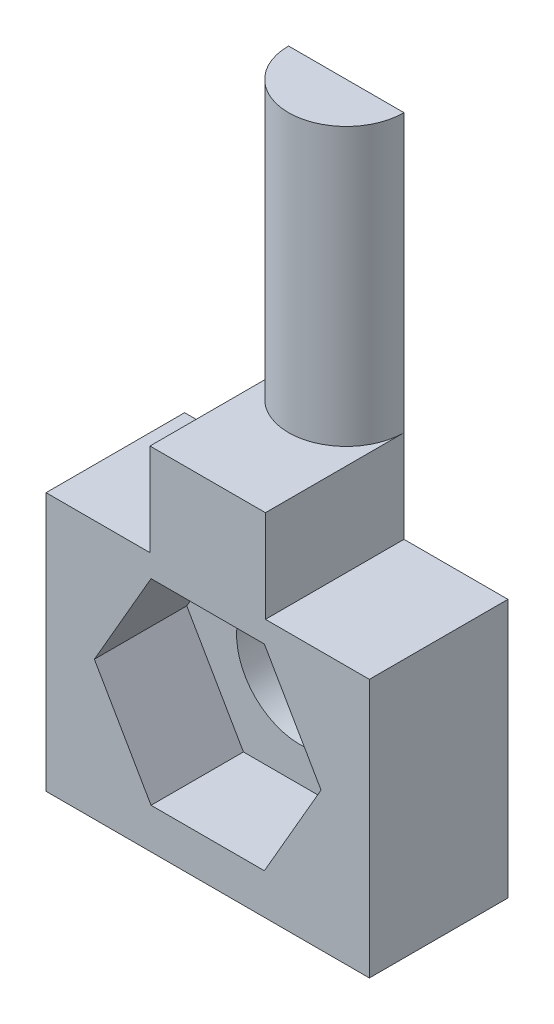
SolidWorks part; units mm, degrees
ref_plane "Alzado" through (0, 0, 0) normal (0, 0, 1) x (1, 0, 0)
ref_plane "Planta" through (0, 0, 0) normal (0, 1, 0) x (1, 0, 0)
ref_plane "Vista lateral" through (0, 0, 0) normal (1, 0, 0) x (0, 0, -1)
sketch "Croquis1" plane through (0, 0, 0) normal (0, 0, 1) x (1, 0, 0)
  line L0 (-9.5, 11.2) -> (-14, 11.2)
  line L1 (0, 0) -> (-14, 0)
  line L2 (0, 0) -> (0, 11.2)
  line L3 (0, 11.2) -> (-4.5, 11.2)
  line L4 (-14, 0) -> (-14, 11.2)
  line L6 (-9.5, 11.2) -> (-9.5, 15.2)
  line L7 (-9.5, 15.2) -> (-4.5, 15.2)
  line L8 (-4.5, 11.2) -> (-4.5, 15.2)
  circle A0 centre (-7, 6) radius 2.75
  dimension "D3" = 5.5
  dimension "D1" = 14
  dimension "D2" = 11.2
  dimension "D4" = 5
  dimension "D5" = 4
  dimension "D6" = 5.2
extrude "Saliente-Extruir1" add sketch "Croquis1" along normal blind 6
sketch "Croquis2" plane through (0, 15.2, 0) normal (0, 1, 0) x (1, 0, 0)
  line L0 (-4.5, 0) -> (-9.5, 0) construction
  line L1 (-9.5, 0) -> (-4.5, 0)
  arc A0 (-9.5, 0) -> (-4.5, 0) centre (-7, 0) ccw
extrude "Saliente-Extruir2" add sketch "Croquis2" along normal blind 12
sketch "Croquis3" plane through (0, 0, 6) normal (0, 0, 1) x (1, 0, 0)
  line L1 (-2.0925, 6) -> (-4.5463, 10.25)
  line L2 (-4.5463, 10.25) -> (-9.4537, 10.25)
  line L3 (-9.4537, 10.25) -> (-11.9075, 6)
  line L4 (-11.9075, 6) -> (-9.4537, 1.75)
  line L5 (-9.4537, 1.75) -> (-4.5463, 1.75)
  line L6 (-4.5463, 1.75) -> (-2.0925, 6)
  circle A0 centre (-7, 6) radius 4.25 construction
  point P1 (-2.0925, 6)
  dimension "D1" = 8.5
extrude "Cortar-Extruir1" cut sketch "Croquis3" against normal blind 4
